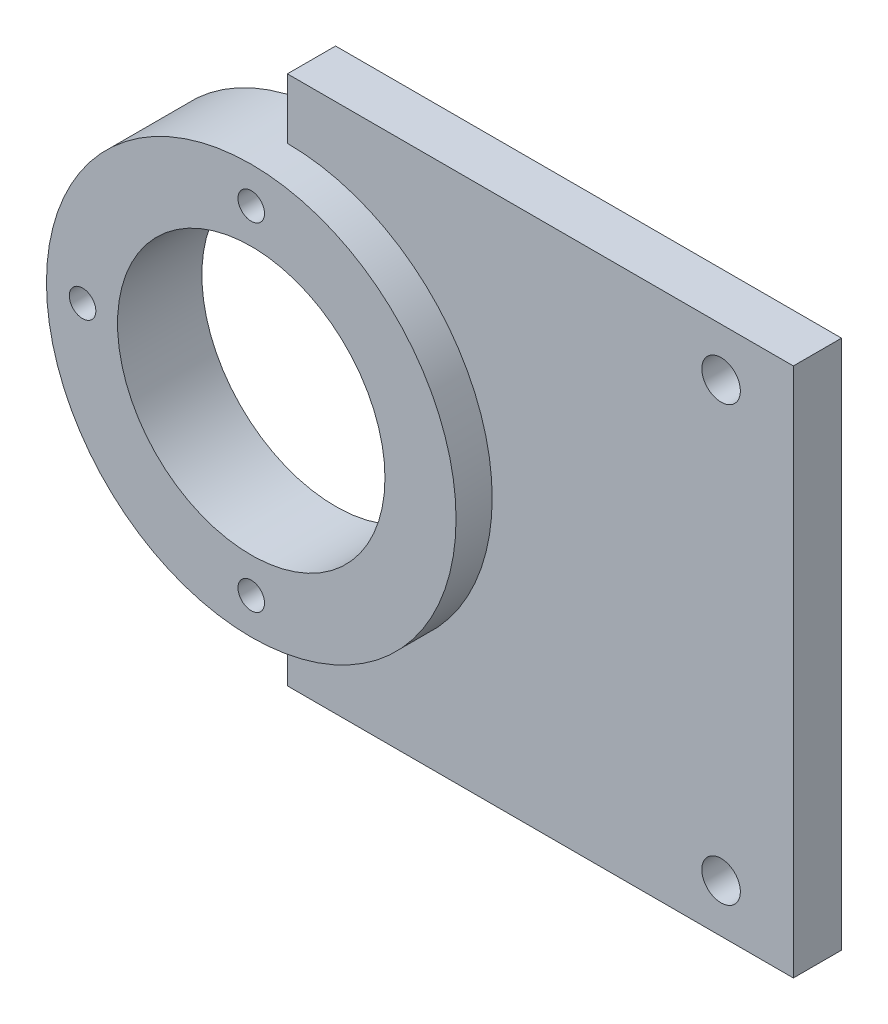
SolidWorks part; units mm, degrees
ref_plane "Front Plane" through (0, 0, 0) normal (0, 0, 1) x (1, 0, 0)
ref_plane "Top Plane" through (0, 0, 0) normal (0, 1, 0) x (1, 0, 0)
ref_plane "Right Plane" through (0, 0, 0) normal (1, 0, 0) x (0, 0, -1)
sketch "Bearing_housing_profile" plane through (0, 0, 0) normal (0, 0, 1) x (1, 0, 0)
  circle A0 centre (0, 0) radius 17
  circle A1 centre (0, 0) radius 11.1
extrude "Bearing_housing" add sketch "Bearing_housing_profile" along normal blind 7
sketch "Mounting_web_profile" plane through (0, 0, 0) normal (0, 0, 1) x (1, 0, 0)
  line L1 (0, -22) -> (42, -22)
  line L2 (0, -22) -> (0, 22)
  line L3 (0, 22) -> (42, 22)
  line L4 (42, -22) -> (42, 22)
extrude "Mounting_web" add sketch "Mounting_web_profile" along normal blind 4
sketch "Bearing_seat_profile" plane through (0, 0, 0) normal (0, 0, 1) x (1, 0, 0)
  circle A0 centre (0, 0) radius 11.1
extrude "Bearing_seat" cut sketch "Bearing_seat_profile" along normal through all from offset 50
sketch "Standoff_fasteners_profile" plane through (0, 0, 0) normal (0, 0, 1) x (1, 0, 0)
  circle A0 centre (36, -18) radius 1.6
  circle A1 centre (36, 18) radius 1.6
extrude "Standoff_fasteners" cut sketch "Standoff_fasteners_profile" along normal through all from offset 50
sketch "Bearing_keeper_fasteners_profile" plane through (0, 0, 0) normal (0, 0, 1) x (1, 0, 0)
  circle A0 centre (-14, 0) radius 1.1
  circle A1 centre (0, -14) radius 1.1
  circle A2 centre (0, 14) radius 1.1
extrude "Bearing_keeper_fasteners" cut sketch "Bearing_keeper_fasteners_profile" along normal through all from offset 50
